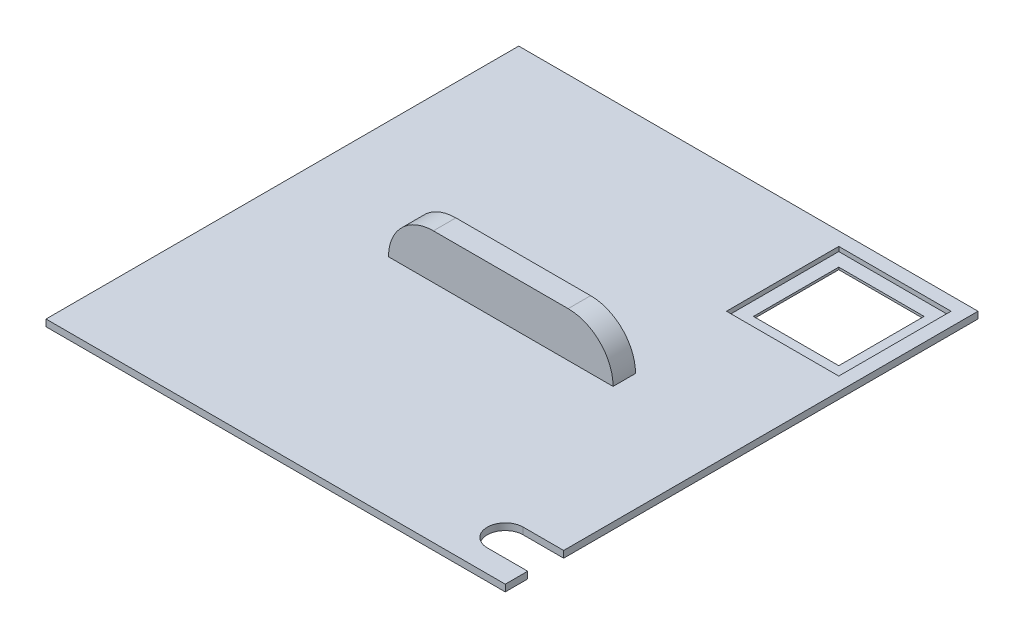
SolidWorks part; units mm, degrees
ref_plane "Front Plane" through (0, 0, 0) normal (0, 0, 1) x (1, 0, 0)
ref_plane "Top Plane" through (0, 0, 0) normal (0, 1, 0) x (1, 0, 0)
ref_plane "Right Plane" through (0, 0, 0) normal (1, 0, 0) x (0, 0, -1)
sketch "Sketch1" plane through (0, 0, 0) normal (0, 1, 0) x (1, 0, 0)
  line L0 (42.125, -39.625) -> (51.125, -39.625)
  line L1 (-51.125, 52.625) -> (51.125, 52.625)
  line L2 (-51.125, 52.625) -> (-51.125, -52.625)
  line L3 (-51.125, -52.625) -> (51.125, -52.625)
  line L4 (51.125, 52.625) -> (51.125, -52.625)
  line L9 (42.125, -47.625) -> (51.125, -47.625)
  arc A0 (42.125, -39.625) -> (42.125, -47.625) centre (42.125, -43.625) ccw
  point P4 (0, 52.625)
  point P6 (-51.125, 0)
  point P8 (42.125, -43.625)
  point P10 (46.125, -43.625)
  dimension "D3" = 8
  dimension "D2" = 9
  dimension "D4" = 9
  dimension "D1" = 105.25
  dimension "D5" = 102.25
extrude "Boss-Extrude1" add sketch "Sketch1" along normal blind 1.5
sketch "Sketch2" plane through (0, 1.5, 0) normal (0, 1, 0) x (1, 0, 0)
  line L1 (-15, 2.5) -> (15, 2.5)
  line L2 (-15, 2.5) -> (-15, -2.5)
  line L3 (-15, -2.5) -> (15, -2.5)
  line L4 (15, 2.5) -> (15, -2.5)
  point P4 (0, 2.5)
  point P6 (15, 0)
  dimension "D1" = 30
  dimension "D2" = 5
extrude "Boss-Extrude2" add sketch "Sketch2" along normal blind 10
sketch "Sketch3" plane through (0, 1.5, 0) normal (0, 1, 0) x (1, 0, 0)
  line L0 (-15, -2.5) -> (-15, 2.5)
  line L3 (-15, 2.5) -> (-15, -2.5) construction
revolve "Revolve-Thin1" add sketch "Sketch3" angle 180 about L0 wall 10
mirror "Mirror1" about plane through (0, 0, 0) normal (1, 0, 0) of "Revolve-Thin1"
sketch "Sketch5" plane through (0, 1.5, 0) normal (0, 1, 0) x (1, 0, 0)
  line L1 (48.125, 24.625) -> (23.125, 24.625)
  line L2 (48.125, 24.625) -> (48.125, 49.625)
  line L3 (48.125, 49.625) -> (23.125, 49.625)
  line L4 (23.125, 24.625) -> (23.125, 49.625)
  line L5 (35.625, 49.625) -> (35.625, 52.625)
  line L6 (-51.125, 52.625) -> (51.125, 52.625) construction
  line L7 (48.125, 37.125) -> (51.125, 37.125)
  line L8 (51.125, -47.625) -> (51.125, -52.625) construction
  point P6 (35.625, 24.625)
  dimension "D1" = 25
  dimension "D2" = 3
extrude "Cut-Extrude1" cut sketch "Sketch5" against normal blind 1 contours L4 L1 L2 L3
sketch "Sketch6" plane through (0, 0.5, 0) normal (0, 1, 0) x (1, 0, 0)
  line L5 (48.125, 24.625) -> (48.125, 49.625) construction
  line L8 (26.125, 46.625) -> (45.125, 46.625)
  line L14 (26.125, 46.625) -> (26.125, 27.625)
  line L15 (26.125, 27.625) -> (45.125, 27.625)
  line L16 (45.125, 46.625) -> (45.125, 27.625)
  line L17 (48.125, 49.625) -> (23.125, 49.625) construction
  line L18 (23.125, 24.625) -> (23.125, 49.625) construction
  dimension "D2" = 3
  dimension "D1" = 3
  dimension "D3" = 3
extrude "Cut-Extrude2" cut sketch "Sketch6" against normal blind 3 contours L16 L8 L14 L15
equation "\"D1@Boss-Extrude2\" = \"RoomSize\" * 0.1"
equation "\"D3@Revolve-Thin1\" = \"RoomSize\" * 0.1"
equation "\"CableSize\"= 8mm"
equation "\"D3@Sketch1\"=\"CableSize\""
equation "\"Windowsize\"= 25mm"
equation "\"WindowThick\"= 1mm"
equation "\"D1@Sketch5\"=\"Windowsize\""
equation "\"D1@Cut-Extrude1\"=\"WindowThick\""
equation "\"CoverThick\"= \"WallsThick\"/2"
equation "\"WindowHoldersize\"= 3mm"
equation "\"RoomSize\"= 100mm"
equation "\"RoomHeight\"= 5cm"
equation "\"WallsThick\"= 6mm"
equation "\"HoleWidth\"= 13mm"
equation "\"MeasureHoleSize\"= 3mm"
equation "\"ModelHeight\"= 1.7mm"
equation "\"HoleHeight\"= 3mm"
equation "\"D2@Sketch5\"=\"WallsThick\"/2"
equation "\"D2@Sketch1\"=\"WallsThick\"*(3/2)"
equation "\"D1@Sketch6\"=\"WindowHoldersize\""
equation "\"D2@Sketch6\"=\"WindowHoldersize\""
equation "\"D3@Sketch6\"=\"WindowHoldersize\""
equation "\"D4@Sketch1\"=\"WallsThick\"*(3/2)"
equation "\"D1@Sketch1\"=(\"RoomSize\" +\"WallsThick\")-\"WallsThick\"/8"
equation "\"D5@Sketch1\"=(\"RoomSize\" +\"WallsThick\"/2)-\"WallsThick\"/8"
